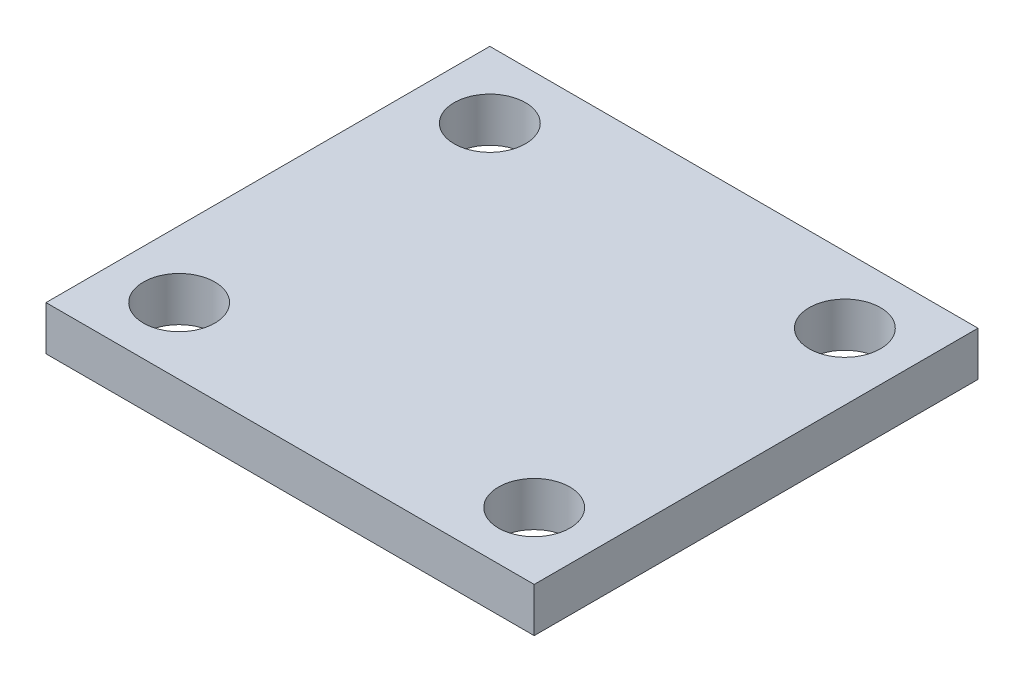
SolidWorks part; units mm, degrees
material "6061 Alloy"
ref_plane "Front Plane" through (0, 0, 0) normal (0, 0, 1) x (1, 0, 0)
ref_plane "Top Plane" through (0, 0, 0) normal (0, 1, 0) x (1, 0, 0)
ref_plane "Right Plane" through (0, 0, 0) normal (1, 0, 0) x (0, 0, -1)
sketch "Sketch1" plane through (0, 0, 0) normal (0, 1, 0) x (1, 0, 0)
  line L1 (-17.4625, -15.875) -> (17.4625, -15.875)
  line L2 (-17.4625, -15.875) -> (-17.4625, 15.875)
  line L3 (-17.4625, 15.875) -> (17.4625, 15.875)
  line L4 (17.4625, -15.875) -> (17.4625, 15.875)
  line L5 (-17.4625, -15.875) -> (17.4625, 15.875) construction
  line L6 (-17.4625, 15.875) -> (17.4625, -15.875) construction
  point P0 (0, 0)
  dimension "D1" = 34.925
  dimension "D2" = 31.75
extrude "Plate" add sketch "Sketch1" along normal mid plane 3.175
hole_wizard "#10 Clearance Hole1" positions "Sketch3" profile "Sketch2" hole size "#10" standard "ANSI Inch" end condition through all
sketch "Sketch3" plane through (0, 1.5875, 0) normal (0, 1, 0) x (1, 0, 0)
  line L12 (12.7, -11.1125) -> (12.7, 11.1125)
  line L13 (12.7, 11.1125) -> (-12.7, 11.1125)
  line L14 (-12.7, 11.1125) -> (-12.7, -11.1125)
  line L15 (-12.7, -11.1125) -> (12.7, -11.1125)
  line L16 (12.7, -11.1125) -> (12.7, 11.1125)
  line L17 (12.7, 11.1125) -> (-12.7, 11.1125)
  line L18 (-12.7, 11.1125) -> (-12.7, -11.1125)
  line L19 (-12.7, -11.1125) -> (12.7, -11.1125)
  point P0 (-12.7, 11.1125)
  point P4 (12.7, 11.1125)
  point P6 (12.7, -11.1125)
  point P10 (-12.7, -11.1125)
  dimension "D1" = 4.7625
sketch "Sketch2" plane through (-12.7, 1.5875, -11.1125) normal (1, 0, 0) x (0, 0, 1)
  line L0 (0, 0) -> (0, 3.175)
  line L1 (0, 3.175) -> (2.5527, 3.175)
  line L2 (2.5527, 3.175) -> (2.5527, 0)
  line L5 (2.5527, 0) -> (0, 0)
  line L11 (0, -6.35) -> (0, 107.95) construction
  dimension "Thru Hole Dia." = 5.1054
  dimension "Thru Hole Depth" = 3.175
